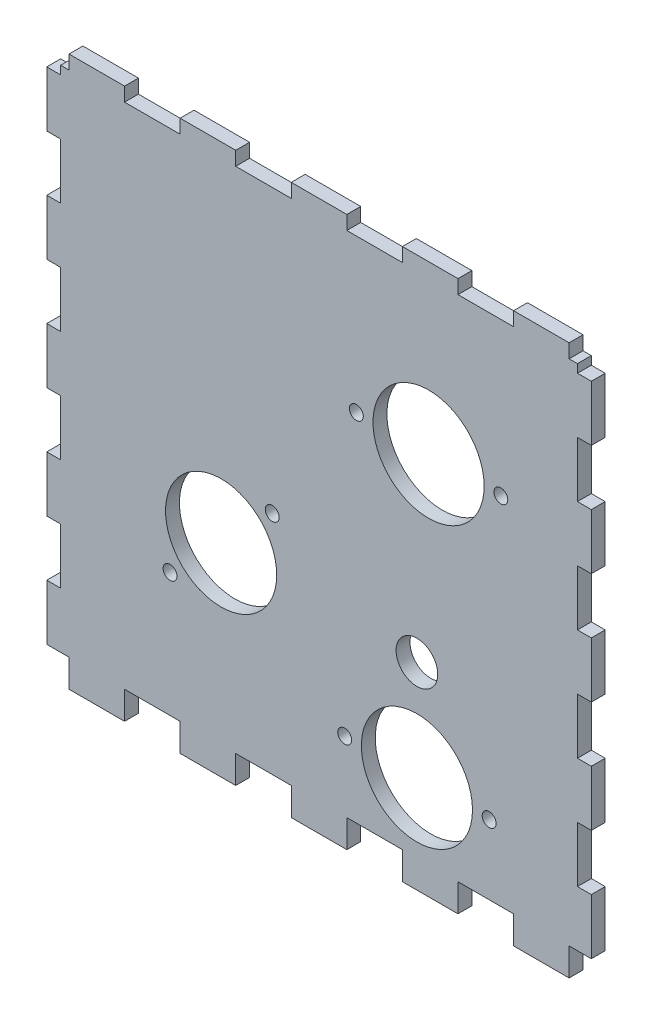
SolidWorks part; units mm, degrees
ref_plane "정면" through (0, 0, 0) normal (0, 0, 1) x (1, 0, 0)
ref_plane "윗면" through (0, 0, 0) normal (0, 1, 0) x (1, 0, 0)
ref_plane "우측면" through (0, 0, 0) normal (1, 0, 0) x (0, 0, -1)
sketch "스케치1" plane through (0, 0, 0) normal (0, 0, 1) x (1, 0, 0)
  line L0 (35.2216, 29.5818) -> (35.2216, -103.0321) construction
  line L1 (-93, 91.5) -> (93, 91.5)
  line L2 (-93, 91.5) -> (-93, -91.5)
  line L3 (-93, -91.5) -> (93, -91.5)
  line L4 (93, 91.5) -> (93, -91.5)
  line L5 (-93, 91.5) -> (93, -91.5) construction
  line L6 (-93, -91.5) -> (93, 91.5) construction
  line L7 (0, 66.5433) -> (0, -75.192) construction
  line L8 (-24.0971, -28.5) -> (-48.104, -28.5) construction
  line L9 (-14.0283, -7.2783) -> (-54.6132, -47.8632) construction
  line L10 (39.4226, 53.7802) -> (39.4226, 16.6513) construction
  circle A0 centre (35.2216, -30.5) radius 7.5
  circle A1 centre (-35.25, -28.5) radius 20
  circle A10 centre (35.2216, -66.5) radius 20
  circle A12 centre (39.4226, 36.5) radius 20
  circle A14 centre (-53.6348, -46.8848) radius 2.5
  circle A15 centre (-16.8652, -10.1152) radius 2.5
  circle A16 centre (65.4226, 36.5) radius 2.5
  circle A17 centre (13.4226, 36.5) radius 2.5
  circle A18 centre (9.2216, -66.5) radius 2.5
  circle A19 centre (61.2216, -66.5) radius 2.5
  point P0 (0, 0)
  dimension "D3" = 40
  dimension "D8" = 5
  dimension "D9" = 52
  dimension "D10" = 15
  dimension "D11" = 25
  dimension "D12" = 40
  dimension "D13" = 40
  dimension "D14" = 55
  dimension "D17" = 5
  dimension "D20" = 5
  dimension "D1" = 186
  dimension "D2" = 183
  dimension "D4" = 35.25
  dimension "D5" = 63
  dimension "D6" = 70.5
  dimension "D7" = 61
  dimension "D15" = 99
  dimension "D16" = 45
  dimension "D18" = 26
  dimension "D19" = 26
  dimension "D21" = 52
extrude "보스-돌출1" add sketch "스케치1" along normal blind 5 contours L4 L1 L2 L3 A0 A1 A18 A19
sketch "스케치2" plane through (0, 0, 5) normal (0, 0, 1) x (1, 0, 0)
  line L5 (93, -91.5) -> (98, -91.5)
  line L6 (93, -91.5) -> (93, -71.5)
  line L7 (93, -71.5) -> (98, -71.5)
  line L8 (98, -91.5) -> (98, -71.5)
  dimension "D1" = 5
  dimension "D2" = 20
extrude "보스-돌출2" add sketch "스케치2" against normal up to surface (5 mm away) contours L7 L8 L5 L6 up to face at (63.7216, -66.5, 0)
pattern_linear "선형 패턴2" count 5 spacing 40 along (0, 1, 0) of "보스-돌출2"
mirror "대칭 복사2" about plane through (0, 0, 0) normal (1, 0, 0) of "선형 패턴2", "보스-돌출2"
sketch "스케치3" plane through (0, 0, 5) normal (0, 0, 1) x (1, 0, 0)
  line L0 (-93, 91.5) -> (93, 91.5) construction
  line L1 (10, 91.5) -> (-10, 91.5)
  line L2 (10, 91.5) -> (10, 96.5)
  line L3 (10, 96.5) -> (-10, 96.5)
  line L4 (-10, 91.5) -> (-10, 96.5)
  line L5 (0, 264.5713) -> (0, -71.5713) construction
  point P9 (0, 96.5)
  dimension "D1" = 5
  dimension "D2" = 20
extrude "보스-돌출3" add sketch "스케치3" against normal up to surface (5 mm away) up to face at (63.7216, -66.5, 0)
pattern_linear "선형 패턴3" count 3 spacing 40 along (1, 0, 0) of "보스-돌출3"
pattern_linear "선형 패턴4" count 3 spacing 40 along (-1, 0, 0) of "보스-돌출3"
sketch "스케치4" plane through (0, 0, 5) normal (0, 0, 1) x (1, 0, 0)
  line L0 (-98, -91.5) -> (98, -91.5) construction
  line L1 (-10, -91.5) -> (10, -91.5)
  line L2 (-10, -91.5) -> (-10, -101.5)
  line L3 (-10, -101.5) -> (10, -101.5)
  line L4 (10, -91.5) -> (10, -101.5)
  line L5 (0, -83.793) -> (0, -117.1866) construction
  dimension "D1" = 20
  dimension "D2" = 10
extrude "보스-돌출4" add sketch "스케치4" against normal up to surface (5 mm away) up to face at (63.7216, -66.5, 0)
pattern_linear "선형 패턴5" count 3 spacing 40 along (1, 0, 0) of "보스-돌출4"
pattern_linear "선형 패턴6" count 3 spacing 40 along (-1, 0, 0) of "선형 패턴5"
